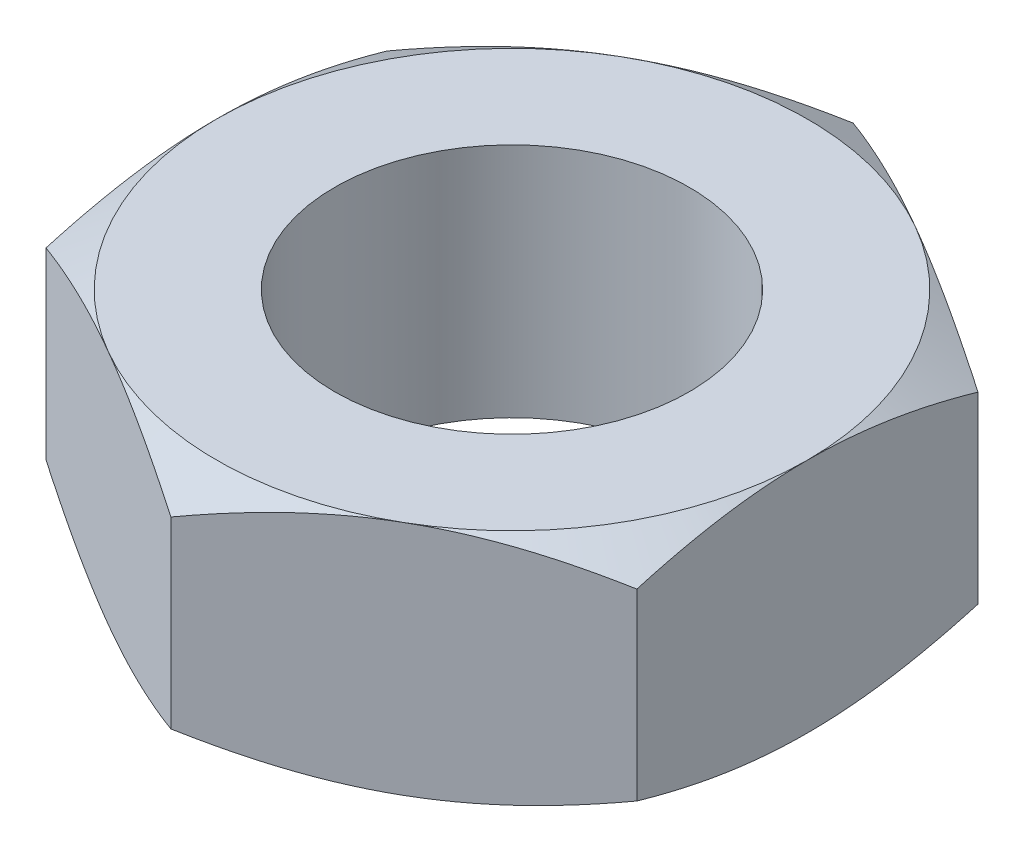
SolidWorks part; units mm, degrees
ref_plane "Front Plane" through (0, 0, 0) normal (0, 0, 1) x (1, 0, 0)
ref_plane "Top Plane" through (0, 0, 0) normal (0, 1, 0) x (1, 0, 0)
ref_plane "Right Plane" through (0, 0, 0) normal (1, 0, 0) x (0, 0, -1)
sketch "Sketch1" plane through (0, 0, 0) normal (0, 1, 0) x (1, 0, 0)
  line L1 (0, 2.8868) -> (-2.5, 1.4434)
  line L2 (-2.5, 1.4434) -> (-2.5, -1.4434)
  line L3 (-2.5, -1.4434) -> (0, -2.8868)
  line L4 (0, -2.8868) -> (2.5, -1.4434)
  line L5 (2.5, -1.4434) -> (2.5, 1.4434)
  line L6 (2.5, 1.4434) -> (0, 2.8868)
  circle A0 centre (0, 0) radius 2.5 construction
  circle A1 centre (0, 0) radius 1.5
  point P10 (0, 0)
  dimension "D1" = 3
  dimension "D2" = 5
extrude "Boss-Extrude1" add sketch "Sketch1" along normal blind 2
sketch "Sketch2" plane through (0, 2, 0) normal (0, 1, 0) x (1, 0, 0)
  circle A0 centre (0, 0) radius 2.5 construction
  circle A1 centre (0, 0) radius 2.5
extrude "Cut-Extrude1" cut sketch "Sketch2" against normal blind 2 draft 60 flip side to cut
ref_plane "Plane1" through (0, 1, 0) normal (0, 1, 0) x (1, 0, 0)
mirror "Mirror1" about plane through (0, 1, 0) normal (0, 1, 0) of "Cut-Extrude1"
